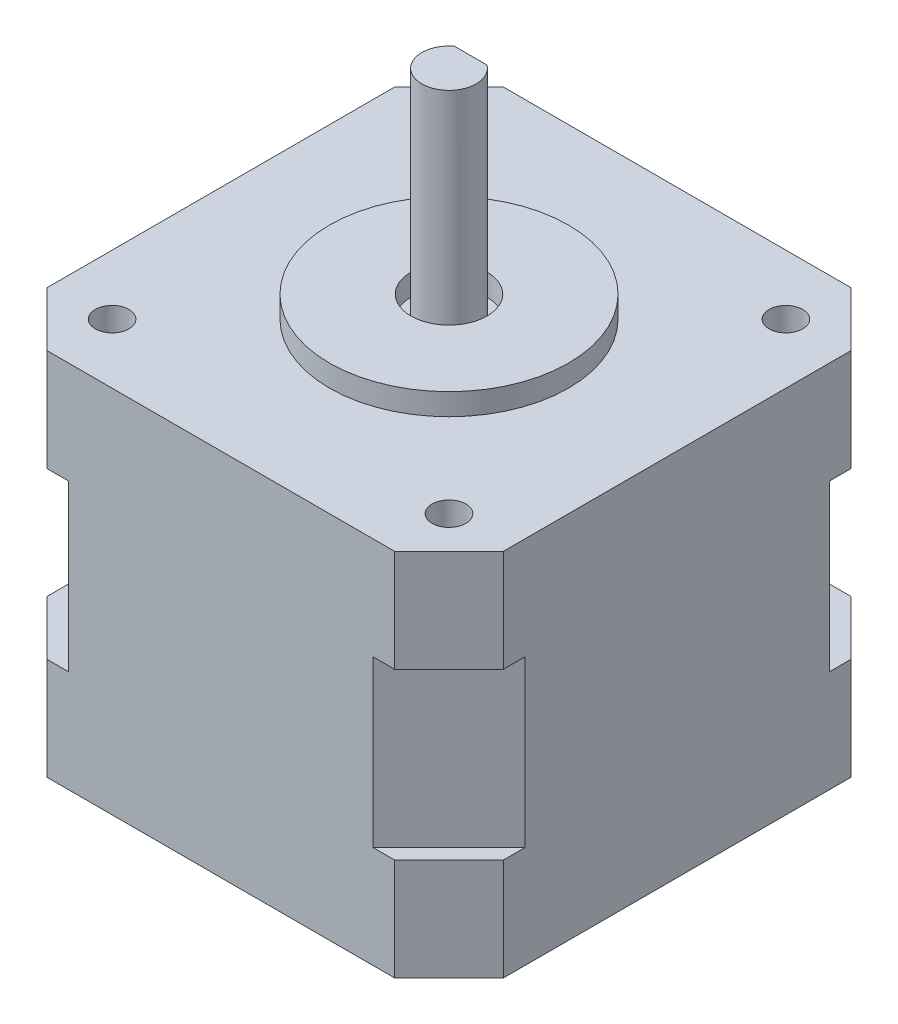
SolidWorks part; units mm, degrees
ref_plane "Front Plane" through (0, 0, 0) normal (0, 0, 1) x (1, 0, 0)
ref_plane "Top Plane" through (0, 0, 0) normal (0, 1, 0) x (1, 0, 0)
ref_plane "Right Plane" through (0, 0, 0) normal (1, 0, 0) x (0, 0, -1)
sketch "Sketch4" plane through (0, 0, 0) normal (0, 1, 0) x (1, 0, 0)
  line L1 (-21, -21) -> (21, -21)
  line L2 (-21, -21) -> (-21, 21)
  line L3 (-21, 21) -> (21, 21)
  line L4 (21, -21) -> (21, 21)
  line L5 (-21, -21) -> (21, 21) construction
  line L6 (-21, 21) -> (21, -21) construction
  point P0 (0, 0)
  dimension "D1" = 42
  dimension "D2" = 42
extrude "Bottom" add sketch "Sketch4" along normal blind 9.4 contours L2 L3 L4 L1
sketch "Sketch6" plane through (0, 9.4, 0) normal (0, 1, 0) x (1, 0, 0)
  line L0 (-21, -14) -> (-14, -21)
  line L1 (-14, -21) -> (14, -21)
  line L2 (-21, -14) -> (-21, 14)
  line L3 (-14, 21) -> (14, 21)
  line L4 (21, -14) -> (21, 14)
  line L5 (-21, -21) -> (21, 21) construction
  line L6 (-21, 21) -> (21, -21) construction
  line L7 (-21, 14) -> (-14, 21)
  line L8 (14, 21) -> (21, 14)
  line L9 (14, -21) -> (21, -14)
  point P0 (0, 0)
  dimension "D1" = 42
  dimension "D2" = 42
extrude "Middle" add sketch "Sketch6" along normal blind 15.2
sketch "Sketch8" plane through (0, 24.6, 0) normal (0, 1, 0) x (1, 0, 0)
  line L1 (-21, -21) -> (21, -21)
  line L2 (-21, -21) -> (-21, 21)
  line L3 (-21, 21) -> (21, 21)
  line L4 (21, -21) -> (21, 21)
  line L5 (-21, -21) -> (21, 21) construction
  line L6 (-21, 21) -> (21, -21) construction
  point P0 (0, 0)
  dimension "D1" = 42
  dimension "D2" = 42
extrude "Top" add sketch "Sketch8" along normal blind 9.4
chamfer "Chamfer1" distance 5 angle 45 8 edges at (21, 4.7, -21) (21, 29.3, -21) (-21, 4.7, 21) (21, 4.7, 21) (21, 29.3, 21) (-21, 29.3, 21) (-21, 4.7, -21) (-21, 29.3, -21)
sketch "Sketch9" plane through (0, 34, 0) normal (0, 1, 0) x (1, 0, 0)
  circle A0 centre (0, 0) radius 11
  circle A1 centre (0, 0) radius 3.5
  dimension "D1" = 22
  dimension "D2" = 7
extrude "Ring" add sketch "Sketch9" along normal blind 2 contours A0 | A1
sketch "Sketch10" plane through (0, 34, 0) normal (0, 1, 0) x (1, 0, 0)
  circle A0 centre (0, 0) radius 2.5
  dimension "D1" = 5
extrude "Shaft" add sketch "Sketch10" along normal blind 20
sketch "Sketch12" plane through (0, 34, 0) normal (0, 1, 0) x (1, 0, 0)
  line L0 (0, 0) -> (0, 23.6682) construction
  line L1 (0, 0) -> (27.1799, 0) construction
  circle A0 centre (15.5, -15.5) radius 1.55
  circle A1 centre (-15.5, -15.5) radius 1.55
  circle A2 centre (-15.5, 15.5) radius 1.55
  circle A3 centre (15.5, 15.5) radius 1.55
  dimension "D1" = 3.1
  dimension "D4" = 31
  dimension "D5" = 31
  dimension "D6" = 15.5
  dimension "D7" = 15.5
  dimension "D8" = 15.5
  dimension "D2" = 2
  dimension "D3" = 2
extrude "Cut-Extrude4" cut sketch "Sketch12" against normal blind 4.5 contours A0 | A1 | A2 | A3
sketch "Sketch15" plane through (0, 0, 0) normal (0, -1, 0) x (1, 0, 0)
  circle A0 centre (15.5, 15.5) radius 1.55
  circle A1 centre (15.5, -15.5) radius 1.55
  circle A2 centre (-15.5, 15.5) radius 1.55
  circle A3 centre (-15.5, -15.5) radius 1.55
  dimension "D1" = 3.1
  dimension "D2" = 3.1
  dimension "D3" = 3.1
  dimension "D4" = 3.1
  dimension "D7" = 31
  dimension "D5" = 31
  dimension "D6" = 31
  dimension "D8" = 15.5
  dimension "D9" = 15.5
  dimension "D10" = 15.5
  dimension "D11" = 15.5
  dimension "D12" = 31
extrude "Cut-Extrude5" cut sketch "Sketch15" against normal blind 10
sketch "Sketch16" plane through (0, 0, 0) normal (0, -1, 0) x (-1, 0, 0)
  circle A0 centre (0, 0) radius 2.5
  dimension "D1" = 5
extrude "Boss-Extrude1" add sketch "Sketch16" along normal blind 10
sketch "Sketch11" plane through (0, 0, 0) normal (1, 0, 0) x (0, 0, -1)
  line L1 (3.4584, 63.2425) -> (2, 63.2425)
  line L2 (3.4584, 63.2425) -> (3.4584, 39)
  line L3 (3.4584, 39) -> (2, 39)
  line L4 (2, 63.2425) -> (2, 39)
  line L5 (2.5, 54) -> (-2.5, 54) construction
  line L6 (-2.5, 54) -> (-2.5, 34) construction
  line L7 (-2.5, 0) -> (-2.5, -10) construction
  line L8 (10.8516, -13.0328) -> (2, -13.0328)
  line L9 (10.8516, -13.0328) -> (10.8516, -1)
  line L10 (10.8516, -1) -> (2, -1)
  line L11 (2, -13.0328) -> (2, -1)
  line L12 (-2.5, -10) -> (2.5, -10) construction
  dimension "D1" = 15
  dimension "D2" = 4.5
  dimension "D3" = 4.5
  dimension "D4" = 9
extrude "Cut-Extrude3" cut sketch "Sketch11" against normal blind 5 and the other way blind 5
